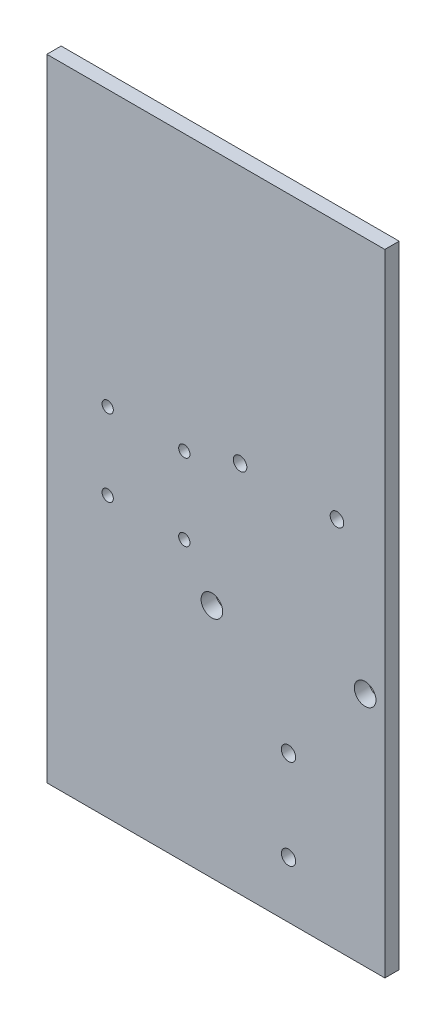
SolidWorks part; units mm, degrees
ref_plane "Alzado" through (0, 0, 0) normal (0, 0, 1) x (1, 0, 0)
ref_plane "Planta" through (0, 0, 0) normal (0, 1, 0) x (1, 0, 0)
ref_plane "Vista lateral" through (0, 0, 0) normal (1, 0, 0) x (0, 0, -1)
sketch "Sketch1" plane through (0, 0, 0) normal (0, 0, 1) x (1, 0, 0)
  line L1 (0, 0) -> (150, 0)
  line L2 (0, 0) -> (0, 280)
  line L3 (0, 280) -> (150, 280)
  line L4 (150, 0) -> (150, 280)
  dimension "D1" = 150
  dimension "D2" = 280
extrude "Boss-Extrude1" add sketch "Sketch1" along normal blind 6.35
sketch "Sketch4" plane through (0, 0, 0) normal (0, 0, 1) x (1, 0, 0)
  line L1 (150, 91.798) -> (150, 117.798)
  line L5 (0, 280) -> (0, 0)
  line L6 (150, 280) -> (0, 280)
  line L7 (150, 0) -> (150, 280)
  line L8 (0, 0) -> (150, 0)
  line L9 (0, 280) -> (0, 0)
  line L10 (150, 280) -> (0, 280)
  line L11 (150, 0) -> (150, 280)
  line L12 (0, 0) -> (150, 0)
  line L20 (96.4681, 50.998) -> (96.4681, -0.002)
  line L21 (92.75, 50.998) -> (96.4681, 50.998)
  line L22 (92.75, 59.1161) -> (92.75, 50.998)
  line L23 (96.4681, 81.998) -> (96.4681, 62.998)
  line L24 (112.5954, 83.998) -> (101.9046, 83.998)
  line L25 (118.0319, 62.998) -> (118.0319, 81.998)
  line L26 (121.75, 50.998) -> (121.75, 59.1161)
  line L27 (118.0319, 35.098) -> (121.75, 50.998)
  line L28 (118.0319, -0.002) -> (118.0319, 35.098)
  line L29 (96.4681, -0.002) -> (118.0319, -0.002)
  circle A2 centre (85.75, 165.628) radius 3
  circle A3 centre (128.75, 165.628) radius 3
  arc A8 (73.25, 99.998) -> (73.25, 109.598) centre (73.25, 104.798) ccw
  arc A9 (73.25, 109.598) -> (73.25, 99.998) centre (73.25, 104.798) ccw
  arc A10 (141.25, 109.598) -> (141.25, 99.998) centre (141.25, 104.798) ccw
  arc A11 (141.25, 99.998) -> (141.25, 109.598) centre (141.25, 104.798) ccw
  circle A14 centre (107.25, 65) radius 3.175
  circle A15 centre (107.25, 25) radius 3.175
  spline S12 degree 3 poles (96.4681, 62.998) (96.4681, 62.7598) (96.4295, 62.5273) (96.2848, 62.0721) (96.1823, 61.8596) (95.9356, 61.4573) (95.7902, 61.2668) (95.4784, 60.914) (95.3107, 60.7497) (94.7813, 60.2839) (94.3924, 60.0085) (93.5923, 59.5213) (93.1772, 59.307) (92.75, 59.1161) knots 0 0 0 0 0.125 0.125 0.25 0.25 0.375 0.375 0.5 0.5 0.75 0.75 1 1 1 1
  spline S13 degree 3 poles (100.6303, 83.9409) (100.2213, 83.9121) (99.8147, 83.8701) (99.01, 83.7425) (98.6118, 83.6578) (98.0257, 83.4723) (97.8309, 83.3999) (97.4564, 83.2285) (97.2763, 83.1299) (96.9397, 82.8896) (96.7849, 82.7495) (96.5458, 82.4079) (96.4681, 82.2066) (96.4681, 81.998) knots 0 0 0 0 0.25 0.25 0.5 0.5 0.625 0.625 0.75 0.75 0.875 0.875 1 1 1 1
  spline S14 degree 3 poles (101.9046, 83.998) (101.4793, 83.998) (101.0548, 83.9708) (100.6303, 83.9409) knots 0 0 0 0 1 1 1 1
  spline S15 degree 3 poles (113.8697, 83.9409) (113.445, 83.9708) (113.0203, 83.998) (112.5954, 83.998) knots 0 0 0 0 1 1 1 1
  spline S16 degree 3 poles (118.0319, 81.998) (118.0319, 82.1017) (118.013, 82.2053) (117.9449, 82.3993) (117.8956, 82.4912) (117.7189, 82.745) (117.5644, 82.886) (117.2312, 83.1252) (117.05, 83.2251) (116.6767, 83.3968) (116.4849, 83.4685) (115.8991, 83.6552) (115.4956, 83.7415) (114.687, 83.87) (114.2792, 83.9121) (113.8697, 83.9409) knots 0 0 0 0 0.0625 0.0625 0.125 0.125 0.25 0.25 0.375 0.375 0.5 0.5 0.75 0.75 1 1 1 1
  spline S17 degree 3 poles (121.75, 59.1161) (121.3201, 59.3082) (120.9016, 59.5246) (120.1002, 60.0135) (119.7129, 60.2884) (119.1852, 60.7537) (119.0181, 60.9177) (118.7074, 61.2698) (118.5627, 61.4597) (118.3167, 61.8616) (118.2138, 62.0757) (118.0706, 62.5275) (118.0319, 62.7597) (118.0319, 62.998) knots 0 0 0 0 0.25 0.25 0.5 0.5 0.625 0.625 0.75 0.75 0.875 0.875 1 1 1 1
  dimension "D2" = 40
  dimension "D3" = 25
  dimension "D1" = 0
extrude "Cut-Extrude1" cut sketch "Sketch4" along normal up to surface (6.35 mm away) contours A15 | A10 A11 | A8 A9 | A3 | A2 | A14 up to face at (75, 140, 6.35)
sketch "Sketch5" plane through (0, 0, 6.35) normal (0, 0, 1) x (-1, 0, 0)
  line L1 (0, 0) -> (-20, 0)
  line L2 (0, 0) -> (-150, 0) construction
  line L3 (-20, 0) -> (-20, -123)
  line L70 (-35, -163) -> (-33.5, -163)
  line L71 (-33.5, -163) -> (-33.5, -162.4403)
  line L72 (-30.5, -162.4403) -> (-30.5, -163)
  line L73 (-30.5, -163) -> (-29, -163)
  line L74 (-29, -163) -> (-28.7113, -162.5)
  line L75 (-28.7113, -162.5) -> (-27, -162.5)
  line L76 (-22.8613, -159.7667) -> (-20, -159)
  line L77 (-20, -159) -> (-20, -152)
  line L78 (-20, -152) -> (-23.5, -151.0622)
  line L79 (-23.5, -151.0622) -> (-23.5, -148.2672)
  line L80 (-23.5, -133.7328) -> (-23.5, -130.9378)
  line L81 (-23.5, -130.9378) -> (-20, -130)
  line L82 (-20, -130) -> (-20, -123)
  line L83 (-20, -123) -> (-22.8613, -122.2333)
  line L84 (-27, -119.5) -> (-28.7113, -119.5)
  line L85 (-28.7113, -119.5) -> (-29, -119)
  line L86 (-29, -119) -> (-30.5, -119)
  line L87 (-30.5, -119) -> (-30.5, -119.5597)
  line L88 (-33.5, -119.5597) -> (-33.5, -119)
  line L89 (-33.5, -119) -> (-35, -119)
  line L90 (-35, -119) -> (-35.866, -120.5)
  line L91 (-35.866, -120.5) -> (-36.7328, -120.5)
  line L92 (-40.7118, -119.5) -> (-47.2882, -119.5)
  line L93 (-55.0227, -122.25) -> (-56.386, -122.25)
  line L94 (-56.386, -122.25) -> (-57.818, -120.818)
  line L95 (-64.182, -127.182) -> (-62.8, -128.564)
  line L96 (-62.8, -128.564) -> (-62.8, -130.0628)
  line L97 (-65.5, -137.7118) -> (-65.5, -144.2882)
  line L98 (-62.8, -151.9372) -> (-62.8, -153.436)
  line L99 (-62.8, -153.436) -> (-64.182, -154.818)
  line L100 (-57.818, -161.182) -> (-56.386, -159.75)
  line L101 (-56.386, -159.75) -> (-55.0227, -159.75)
  line L102 (-47.2882, -162.5) -> (-40.7118, -162.5)
  line L103 (-36.7328, -161.5) -> (-35.866, -161.5)
  line L104 (-35.866, -161.5) -> (-35, -163)
  arc A1 (-61, -155.5) -> (-61, -160.5) centre (-61, -158) ccw
  arc A3 (-27, -155.5) -> (-27, -160.5) centre (-27, -158) ccw
  arc A5 (-27, -121.5) -> (-27, -126.5) centre (-27, -124) ccw
  arc A7 (-27, -126.5) -> (-27, -121.5) centre (-27, -124) ccw
  arc A9 (-27, -160.5) -> (-27, -155.5) centre (-27, -158) ccw
  arc A11 (-61, -160.5) -> (-61, -155.5) centre (-61, -158) ccw
  arc A13 (-61, -126.5) -> (-61, -121.5) centre (-61, -124) ccw
  arc A28 (-32, -158.75) -> (-33.5, -162.4403) centre (-32, -160.9) ccw
  arc A29 (-30.5, -162.4403) -> (-32, -158.75) centre (-32, -160.9) ccw
  arc A30 (-27, -162.5) -> (-22.8613, -159.7667) centre (-27, -158) ccw
  arc A31 (-23.5, -148.2672) -> (-23.5, -133.7328) centre (-44, -141) ccw
  arc A32 (-22.8613, -122.2333) -> (-27, -119.5) centre (-27, -124) ccw
  arc A33 (-33.5, -119.5597) -> (-30.5, -119.5597) centre (-32, -121.1) ccw
  arc A34 (-36.7328, -120.5) -> (-40.7118, -119.5) centre (-44, -141) ccw
  arc A35 (-47.2882, -119.5) -> (-55.0227, -122.25) centre (-44, -141) ccw
  arc A36 (-57.818, -120.818) -> (-64.182, -127.182) centre (-61, -124) ccw
  arc A37 (-62.8, -130.0628) -> (-65.5, -137.7118) centre (-44, -141) ccw
  arc A38 (-65.5, -144.2882) -> (-62.8, -151.9372) centre (-44, -141) ccw
  arc A39 (-64.182, -154.818) -> (-57.818, -161.182) centre (-61, -158) ccw
  arc A40 (-55.0227, -159.75) -> (-47.2882, -162.5) centre (-44, -141) ccw
  arc A41 (-40.7118, -162.5) -> (-36.7328, -161.5) centre (-44, -141) ccw
  arc A43 (-61, -121.5) -> (-61, -126.5) centre (-61, -124) ccw
  dimension "D1" = 20
  dimension "D2" = 123
extrude "Cut-Extrude2" cut sketch "Sketch5" against normal up to surface (6.35 mm away) contours A13 A43 | A7 A5 | A9 A3 | A11 A1 up to face at (110.425, 25, 0)
